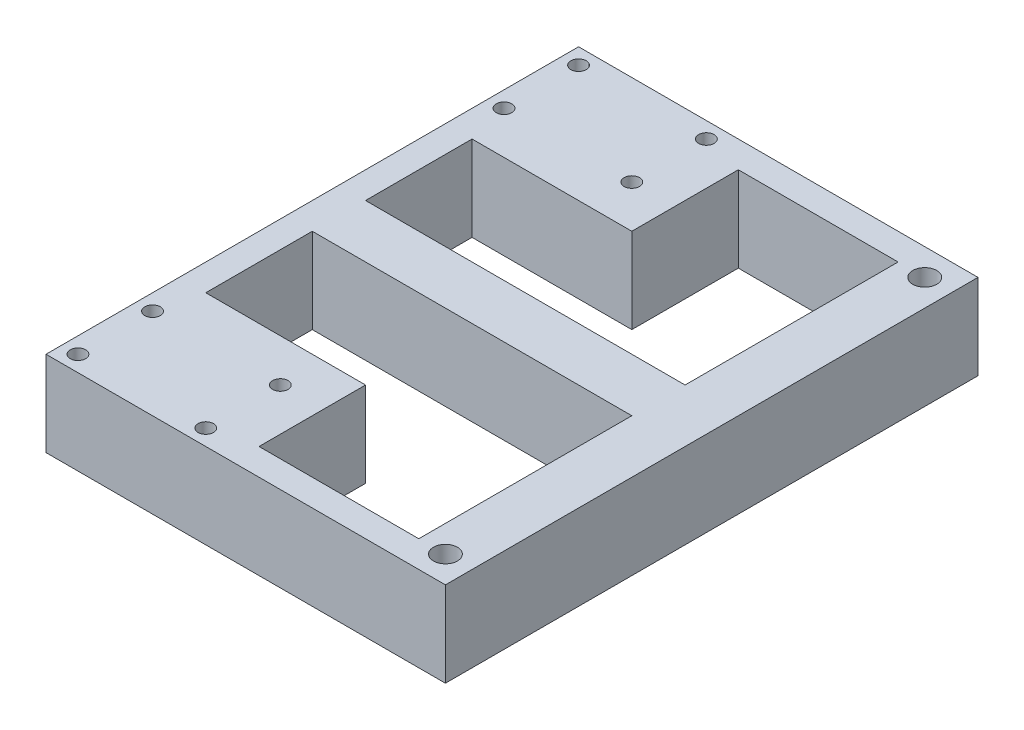
SolidWorks part; units mm, degrees
ref_plane "前视基准面" through (0, 0, 0) normal (0, 0, 1) x (1, 0, 0)
ref_plane "上视基准面" through (0, 0, 0) normal (0, 1, 0) x (1, 0, 0)
ref_plane "右视基准面" through (0, 0, 0) normal (1, 0, 0) x (0, 0, -1)
other "Configuration Table"
sketch "草图1" plane through (0, 0, 0) normal (0, 1, 0) x (1, 0, 0)
  line L1 (0, 0) -> (-75, 0)
  line L2 (0, 0) -> (0, 100)
  line L3 (0, 100) -> (-75, 100)
  line L4 (-75, 0) -> (-75, 100)
  dimension "D1" = 100
  dimension "D2" = 75
extrude "凸台-拉伸1" add sketch "草图1" along normal blind 16
sketch "草图6" plane through (0, 16, 0) normal (0, 1, 0) x (1, 0, 0)
  line L0 (-75, 100) -> (-75, 0) construction
  line L1 (-40, 45) -> (-5, 45)
  line L2 (-40, 25) -> (-40, 5)
  line L3 (-40, 5) -> (-5, 5)
  line L4 (-5, 45) -> (-5, 5)
  line L5 (0, 0) -> (0, 100) construction
  line L6 (-75, 0) -> (0, 0) construction
  line L7 (-75, 50) -> (-60.5255, 50) construction
  line L8 (-40, 95) -> (-5, 95)
  line L9 (-5, 55) -> (-5, 95)
  line L10 (-40, 55) -> (-5, 55)
  line L11 (-40, 75) -> (-40, 95)
  line L12 (-40, 75) -> (-70, 75)
  line L13 (-40, 45) -> (-70, 45)
  line L15 (-40, 25) -> (-70, 25)
  line L16 (-70, 45) -> (-70, 25)
  line L17 (-40, 55) -> (-70, 55)
  line L18 (-70, 55) -> (-70, 75)
  dimension "D1" = 35
  dimension "D2" = 5
  dimension "D3" = 5
  dimension "D4" = 40
  dimension "D5" = 30
  dimension "D6" = 20
extrude "切除-拉伸5" cut sketch "草图6" against normal up to next
sketch "草图8" plane through (0, 16, 0) normal (0, 1, 0) x (1, 0, 0)
  line L0 (-75, 100) -> (-72, 100) construction
  line L1 (0, 100) -> (-75, 100) construction
  line L2 (-72, 100) -> (-72, 97) construction
  line L3 (-72, 97) -> (-48, 97) construction
  line L4 (-48, 97) -> (-48, 83) construction
  line L5 (-48, 83) -> (-72, 83) construction
  line L6 (-75, 50) -> (-51.1245, 50) construction
  line L7 (-75, 100) -> (-75, 0) construction
  line L8 (-48, 17) -> (-72, 17) construction
  line L9 (-48, 3) -> (-48, 17) construction
  line L10 (-72, 3) -> (-48, 3) construction
  line L11 (-72, 0) -> (-72, 3) construction
  line L12 (-75, 0) -> (-72, 0) construction
  circle A0 centre (-72, 97) radius 1.45
  circle A1 centre (-72, 83) radius 1.45
  circle A2 centre (-48, 97) radius 1.45
  circle A3 centre (-48, 83) radius 1.45
  circle A4 centre (-48, 17) radius 1.45
  circle A5 centre (-48, 3) radius 1.45
  circle A6 centre (-72, 17) radius 1.45
  circle A7 centre (-72, 3) radius 1.45
  dimension "D6" = 2.9
  dimension "D7" = 2.9
  dimension "D8" = 2.9
  dimension "D9" = 2.9
  dimension "D1" = 3
  dimension "D2" = 3
  dimension "D3" = 24
  dimension "D4" = 14
  dimension "D5" = 24
extrude "切除-拉伸7" cut sketch "草图8" against normal through all
sketch "草图9" plane through (-5, 0, 0) normal (-1, 0, 0) x (0, 0, 1)
  line L0 (-45, 0) -> (-5, 0) construction
  line L1 (-5, 0) -> (-5, 16) construction
  line L2 (-5, 16) -> (-45, 16) construction
  line L3 (-45, 16) -> (-45, 0) construction
  line L4 (-95, 0) -> (-55, 0) construction
  line L5 (-55, 0) -> (-55, 16) construction
  line L6 (-55, 16) -> (-95, 16) construction
  line L7 (-95, 16) -> (-95, 0) construction
  line L8 (-45, 0) -> (-5, 0)
  line L9 (-5, 0) -> (-5, 16)
  line L10 (-5, 16) -> (-45, 16)
  line L11 (-45, 16) -> (-45, 0)
  line L12 (-95, 0) -> (-55, 0)
  line L13 (-55, 0) -> (-55, 16)
  line L14 (-55, 16) -> (-95, 16)
  line L15 (-95, 16) -> (-95, 0)
extrude "凸台-拉伸2" add sketch "草图9" along normal blind 5
sketch "草图10" plane through (0, 16, 0) normal (0, 1, 0) x (1, 0, 0)
  line L0 (0, 100) -> (0, 95) construction
  line L1 (0, 0) -> (0, 100) construction
  line L2 (0, 95) -> (-5, 95) construction
  line L3 (0, 50) -> (-16.1785, 50) construction
  circle A0 centre (-5, 95) radius 2.25
  circle A1 centre (-5, 5) radius 2.25
  dimension "D3" = 4.5
  dimension "D1" = 5
  dimension "D2" = 5
extrude "切除-拉伸8" cut sketch "草图10" against normal blind 5
sketch "草图11" plane through (0, 0, 0) normal (0, -1, 0) x (1, 0, 0)
  circle A0 centre (-5, -95) radius 2.25 construction
  circle A1 centre (-5, -5) radius 2.25 construction
  circle A2 centre (-5, -95) radius 2.25
  circle A3 centre (-5, -5) radius 2.25
extrude "切除-拉伸9" cut sketch "草图11" against normal blind 5
